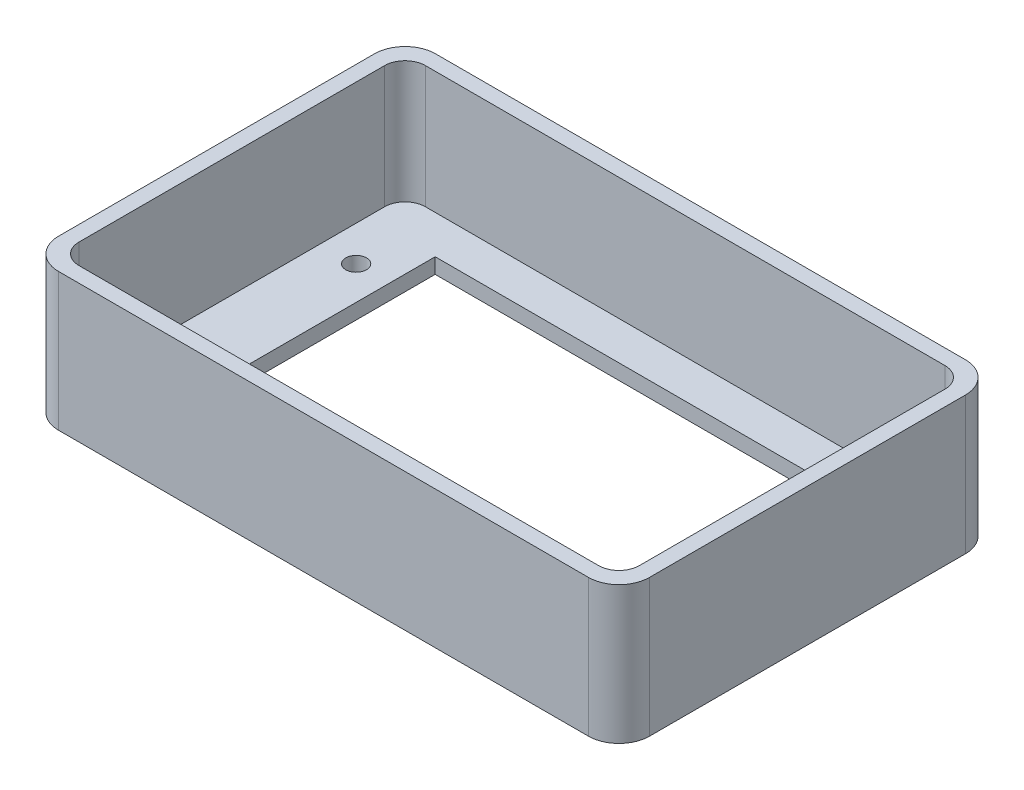
SolidWorks part; units mm, degrees
ref_plane "Front Plane" through (0, 0, 0) normal (0, 0, 1) x (1, 0, 0)
ref_plane "Top Plane" through (0, 0, 0) normal (0, 1, 0) x (1, 0, 0)
ref_plane "Right Plane" through (0, 0, 0) normal (1, 0, 0) x (0, 0, -1)
sketch "Sketch1" plane through (0, 0, 0) normal (0, 1, 0) x (1, 0, 0)
  line L1 (69.85, 43.18) -> (-69.85, 43.18)
  line L2 (69.85, 43.18) -> (69.85, -43.18)
  line L3 (69.85, -43.18) -> (-69.85, -43.18)
  line L4 (-69.85, 43.18) -> (-69.85, -43.18)
  line L5 (69.85, 43.18) -> (-69.85, -43.18) construction
  line L6 (69.85, -43.18) -> (-69.85, 43.18) construction
  line L7 (73.66, -46.99) -> (-73.66, -46.99)
  line L8 (73.66, -46.99) -> (73.66, 46.99)
  line L9 (73.66, 46.99) -> (-73.66, 46.99)
  line L10 (-73.66, -46.99) -> (-73.66, 46.99)
  line L11 (73.66, -46.99) -> (-73.66, 46.99) construction
  line L12 (73.66, 46.99) -> (-73.66, -46.99) construction
  point P0 (0, 0)
  point P7 (0, 0)
  dimension "D1" = 3.81
  dimension "D2" = 3.81
  dimension "D3" = 86.36
  dimension "D4" = 139.7
extrude "Boss-Extrude1" add sketch "Sketch1" along normal blind 30.48
sketch "Sketch2" plane through (0, 0, 0) normal (0, -1, 0) x (-1, 0, 0)
  line L1 (73.66, -46.99) -> (-73.66, -46.99)
  line L2 (73.66, -46.99) -> (73.66, 46.99)
  line L3 (73.66, 46.99) -> (-73.66, 46.99)
  line L4 (-73.66, -46.99) -> (-73.66, 46.99)
extrude "Boss-Extrude2" add sketch "Sketch2" along normal blind 3.81
fillet "Fillet1" radius 7.62 4 edges at (-73.66, 13.335, -46.99) (-73.66, 13.335, 46.99) (73.66, 13.335, 46.99) (73.66, 13.335, -46.99)
fillet "Fillet2" radius 5.08 4 edges at (69.85, 15.24, 43.18) (-69.85, 15.24, 43.18) (-69.85, 15.24, -43.18) (69.85, 15.24, -43.18)
sketch "Sketch4" plane through (0, -3.81, 0) normal (0, -1, 0) x (1, 0, 0)
  line L1 (52.7558, -33.6042) -> (-52.7558, -33.6042)
  line L2 (52.7558, -33.6042) -> (52.7558, 33.6042)
  line L3 (52.7558, 33.6042) -> (-52.7558, 33.6042)
  line L4 (-52.7558, -33.6042) -> (-52.7558, 33.6042)
  line L5 (52.7558, -33.6042) -> (-52.7558, 33.6042) construction
  line L6 (52.7558, 33.6042) -> (-52.7558, -33.6042) construction
  point P0 (0, 0)
  dimension "D1" = 67.2084
  dimension "D2" = 105.5116
extrude "Cut-Extrude2" cut sketch "Sketch4" against normal up to next
sketch "Sketch5" plane through (0, 0, 0) normal (0, 1, 0) x (1, 0, 0)
  circle A1 centre (-61.0842, -22.2208) radius 2.58
  circle A2 centre (61.0958, -22.2208) radius 2.58
  circle A3 centre (61.0958, 22.2292) radius 2.58
  circle A4 centre (-61.0842, 22.2292) radius 2.58
extrude "Cut-Extrude3" cut sketch "Sketch5" against normal up to next
